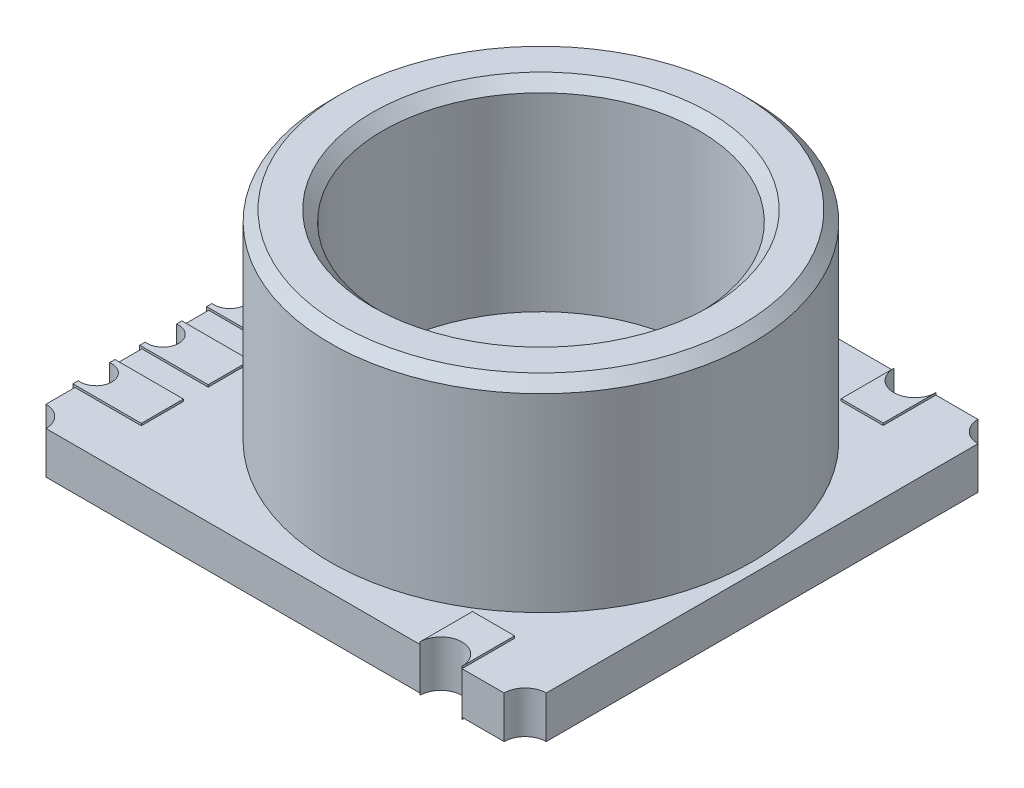
SolidWorks part; units mm, degrees
ref_plane "Спереди" through (0, 0, 0) normal (0, 0, 1) x (1, 0, 0)
ref_plane "Сверху" through (0, 0, 0) normal (0, 1, 0) x (1, 0, 0)
ref_plane "Справа" through (0, 0, 0) normal (1, 0, 0) x (0, 0, -1)
sketch "Эскиз1" plane through (0, 0, 0) normal (0, 1, 0) x (1, 0, 0)
  line L1 (4.75, -4.5) -> (-4.75, -4.5)
  line L2 (4.75, -4.5) -> (4.75, 4.5)
  line L3 (4.75, 4.5) -> (-4.75, 4.5)
  line L4 (-4.75, -4.5) -> (-4.75, 4.5)
  line L5 (4.75, -4.5) -> (-4.75, 4.5) construction
  line L6 (4.75, 4.5) -> (-4.75, -4.5) construction
  point P0 (0, 0)
  dimension "D1" = 9
  dimension "D2" = 9.5
extrude "Бобышка-Вытянуть1" add sketch "Эскиз1" along normal blind 0.8
sketch "Эскиз4" plane through (0, 0, 0) normal (0, -1, 0) x (1, 0, 0)
  circle A0 centre (-4.75, -4.5) radius 0.4
  circle A1 centre (4.75, -4.5) radius 0.4
  circle A2 centre (-4.75, 4.5) radius 0.4
  circle A3 centre (4.75, 4.5) radius 0.4
  dimension "D9" = 0.8
  dimension "D1" = 4.5
  dimension "D2" = 4.75
  dimension "D3" = 4.75
  dimension "D4" = 4.5
  dimension "D5" = 4.5
  dimension "D6" = 4.75
  dimension "D7" = 4.75
  dimension "D8" = 4.5
extrude "Вырез-Вытянуть1" cut sketch "Эскиз4" against normal through all
sketch "Эскиз6" plane through (0, 0.8, 0) normal (0, 1, 0) x (1, 0, 0)
  line L0 (4.35, 4.5) -> (-4.35, 4.5) construction
  line L1 (-3.49, 2.8) -> (-4.79, 2.8)
  line L2 (-3.49, 2.8) -> (-3.49, 3.6)
  line L3 (-3.49, 3.6) -> (-4.79, 3.6)
  line L4 (-4.79, 2.8) -> (-4.79, 3.6)
  line L5 (-3.49, 2.8) -> (-4.79, 3.6) construction
  line L6 (-3.49, 3.6) -> (-4.79, 2.8) construction
  line L8 (-3.49, 1.53) -> (-4.79, 1.53)
  line L9 (-3.49, 1.53) -> (-3.49, 2.33)
  line L10 (-3.49, 2.33) -> (-4.79, 2.33)
  line L11 (-4.79, 1.53) -> (-4.79, 2.33)
  line L12 (-3.49, 1.53) -> (-4.79, 2.33) construction
  line L13 (-3.49, 2.33) -> (-4.79, 1.53) construction
  line L14 (-3.49, 0.26) -> (-4.79, 0.26)
  line L15 (-3.49, 0.26) -> (-3.49, 1.06)
  line L16 (-3.49, 1.06) -> (-4.79, 1.06)
  line L17 (-4.79, 0.26) -> (-4.79, 1.06)
  line L18 (-3.49, 0.26) -> (-4.79, 1.06) construction
  line L19 (-3.49, 1.06) -> (-4.79, 0.26) construction
  line L20 (-3.49, -1.01) -> (-4.79, -1.01)
  line L21 (-3.49, -1.01) -> (-3.49, -0.21)
  line L22 (-3.49, -0.21) -> (-4.79, -0.21)
  line L23 (-4.79, -1.01) -> (-4.79, -0.21)
  line L24 (-3.49, -1.01) -> (-4.79, -0.21) construction
  line L25 (-3.49, -0.21) -> (-4.79, -1.01) construction
  line L26 (-3.49, -2.28) -> (-4.79, -2.28)
  line L27 (-3.49, -2.28) -> (-3.49, -1.48)
  line L28 (-3.49, -1.48) -> (-4.79, -1.48)
  line L29 (-4.79, -2.28) -> (-4.79, -1.48)
  line L30 (-3.49, -2.28) -> (-4.79, -1.48) construction
  line L31 (-3.49, -1.48) -> (-4.79, -2.28) construction
  line L32 (-3.49, -3.55) -> (-4.79, -3.55)
  line L33 (-3.49, -3.55) -> (-3.49, -2.75)
  line L34 (-3.49, -2.75) -> (-4.79, -2.75)
  line L35 (-4.79, -3.55) -> (-4.79, -2.75)
  line L36 (-3.49, -3.55) -> (-4.79, -2.75) construction
  line L37 (-3.49, -2.75) -> (-4.79, -3.55) construction
  line L38 (3.55, 3.5) -> (2.75, 3.5)
  line L39 (3.55, 3.5) -> (3.55, 4.5)
  line L40 (3.55, 4.5) -> (2.75, 4.5)
  line L41 (2.75, 3.5) -> (2.75, 4.5)
  line L42 (3.55, 3.5) -> (2.75, 4.5) construction
  line L43 (3.55, 4.5) -> (2.75, 3.5) construction
  line L44 (4.75, -4.1) -> (4.75, 4.1) construction
  line L45 (0, 0) -> (7.2422, 0) construction
  line L46 (3.55, -4.5) -> (2.75, -3.5) construction
  line L47 (3.55, -3.5) -> (2.75, -4.5) construction
  line L48 (2.75, -3.5) -> (2.75, -4.5)
  line L49 (3.55, -4.5) -> (2.75, -4.5)
  line L50 (3.55, -3.5) -> (3.55, -4.5)
  line L51 (3.55, -3.5) -> (2.75, -3.5)
  line L53 (-4.75, 4.1) -> (-4.75, -4.1) construction
  line L55 (4.35, 4.5) -> (-4.35, 4.5) construction
  point P0 (-4.14, 3.2)
  point P9 (3.15, 4)
  point P11 (-4.14, 1.93)
  point P16 (-4.14, 0.66)
  point P21 (-4.14, -0.61)
  point P26 (-4.14, -1.88)
  point P31 (-4.14, -3.15)
  point P47 (3.15, -4)
  dimension "D1" = 1.3
  dimension "D2" = 0.8
  dimension "D3" = 1.3
  dimension "D5" = 0.8
  dimension "D6" = 1
  dimension "D7" = 1.6
  dimension "D8" = 1.27
  dimension "D9" = 0.04
  dimension "D4" = 6
extrude "Бобышка-Вытянуть2" add sketch "Эскиз6" along normal blind 0.04 and the other way blind 0.84
sketch "Эскиз5" plane through (0, 0, 0) normal (0, -1, 0) x (1, 0, 0)
  line L0 (4.35, -4.5) -> (3.55, -4.5) construction
  line L2 (-4.75, -4.1) -> (-4.75, -3.6) construction
  line L3 (-4.35, 4.5) -> (2.75, 4.5) construction
  line L4 (4.75, 4.1) -> (4.75, -4.1) construction
  circle A0 centre (3.15, 4.5) radius 0.4
  circle A1 centre (3.15, -4.5) radius 0.4
  circle A2 centre (-4.75, -3.2) radius 0.3
  circle A3 centre (-4.75, -1.93) radius 0.3
  circle A4 centre (-4.75, -0.66) radius 0.3
  circle A5 centre (-4.75, 0.61) radius 0.3
  circle A6 centre (-4.75, 1.88) radius 0.3
  circle A7 centre (-4.75, 3.15) radius 0.3
  dimension "D1" = 0.8
  dimension "D2" = 0.8
  dimension "D3" = 0.6
  dimension "D4" = 1.3
  dimension "D5" = 1.27
  dimension "D6" = 1.27
  dimension "D7" = 1.27
  dimension "D8" = 1.27
  dimension "D9" = 1.27
  dimension "D10" = 1.6
  dimension "D11" = 1.6
extrude "Вырез-Вытянуть2" cut sketch "Эскиз5" against normal through all and the other way through all
sketch "Эскиз7" plane through (0, 0.8, 0) normal (0, 1, 0) x (1, 0, 0)
  line L1 (4.75, -4.1) -> (4.75, 4.1) construction
  circle A0 centre (0.55, 0) radius 3
  circle A1 centre (0.55, 0) radius 4
  dimension "D1" = 6
  dimension "D2" = 8
  dimension "D3" = 4.2
extrude "Бобышка-Вытянуть3" add sketch "Эскиз7" along normal blind 3.8
chamfer "Фаска1" distance 0.2 angle 45 1 edges at (0.55, 4.6, 4)
chamfer "Фаска2" distance 0.2 angle 45 1 edges at (0.55, 4.6, 3)
